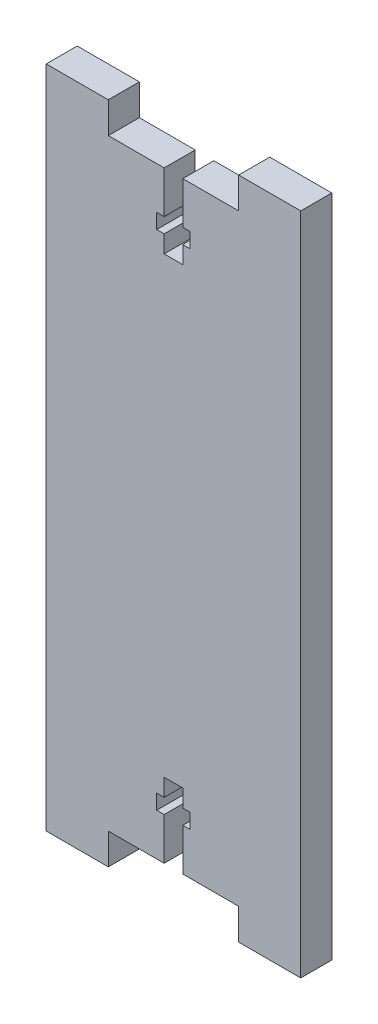
SolidWorks part; units mm, degrees
ref_plane "Plano frontal" through (0, 0, 0) normal (0, 0, 1) x (1, 0, 0)
ref_plane "Plano superior" through (0, 0, 0) normal (0, 1, 0) x (1, 0, 0)
ref_plane "Plano direito" through (0, 0, 0) normal (1, 0, 0) x (0, 0, -1)
sketch "Model" plane through (0, 0, 0) normal (0, 0, 1) x (1, 0, 0)
  line L0 (52.0021, 87.5) -> (61, 87.5)
  line L1 (61, 87.5) -> (61, 92.5)
  line L2 (61, 92.5) -> (71, 92.5)
  line L3 (71, 92.5) -> (71, -14.5)
  line L4 (71, -14.5) -> (61, -14.5)
  line L5 (61, -14.5) -> (61, -9.5)
  line L6 (61, -9.5) -> (52.0021, -9.5)
  line L7 (52.0021, -9.5) -> (52.0021, -2.7)
  line L8 (52.0021, -2.7) -> (53.2021, -2.7)
  line L9 (53.2021, -2.7) -> (53.2021, -0.3)
  line L10 (53.2021, -0.3) -> (52.0021, -0.3)
  line L11 (52.0021, -0.3) -> (52.0021, 2.5)
  line L12 (52.0021, 2.5) -> (49.0021, 2.5)
  line L13 (49.0021, 2.5) -> (49.0021, -0.3)
  line L14 (49.0021, -0.3) -> (47.8021, -0.3)
  line L15 (47.8021, -0.3) -> (47.8021, -2.7)
  line L16 (47.8021, -2.7) -> (49.0021, -2.7)
  line L17 (49.0021, -2.7) -> (49.0021, -9.5)
  line L18 (49.0021, -9.5) -> (40.0041, -9.5)
  line L19 (40.0041, -9.5) -> (40.0041, -14.5)
  line L20 (40.0041, -14.5) -> (30.0041, -14.5)
  line L21 (30.0041, -14.5) -> (30.0041, 92.5)
  line L22 (30.0041, 92.5) -> (40.0041, 92.5)
  line L23 (40.0041, 92.5) -> (40.0041, 87.5)
  line L24 (40.0041, 87.5) -> (49.0021, 87.5)
  line L25 (49.0021, 87.5) -> (49.0021, 80.7)
  line L26 (49.0021, 80.7) -> (47.8021, 80.7)
  line L27 (47.8021, 80.7) -> (47.8021, 78.3)
  line L28 (47.8021, 78.3) -> (49.0021, 78.3)
  line L29 (49.0021, 78.3) -> (49.0021, 75.5)
  line L30 (49.0021, 75.5) -> (52.0021, 75.5)
  line L31 (52.0021, 75.5) -> (52.0021, 78.3)
  line L32 (52.0021, 78.3) -> (53.2021, 78.3)
  line L33 (53.2021, 78.3) -> (53.2021, 80.7)
  line L34 (53.2021, 80.7) -> (52.0021, 80.7)
  line L35 (52.0021, 80.7) -> (52.0021, 87.5)
extrude "Ressalto-extrusão1" add sketch "Model" along normal blind 5
